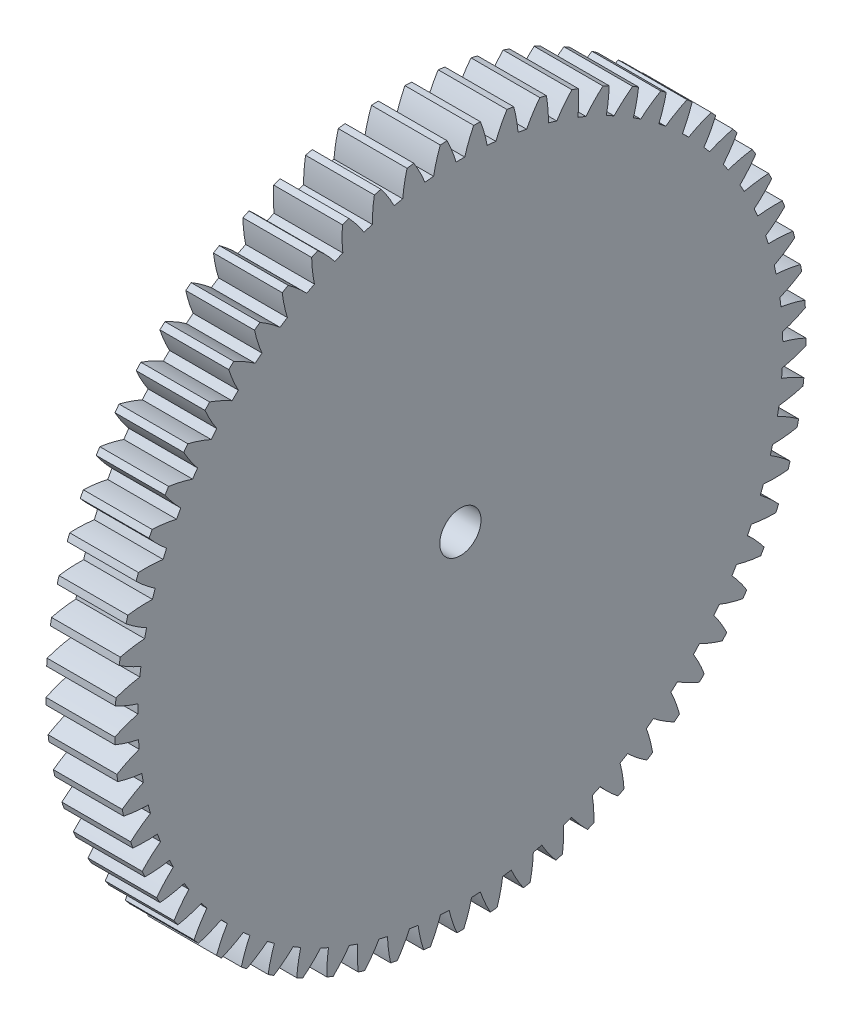
SolidWorks part; units mm, degrees
ref_plane "Plane1" through (0, 0, 0) normal (0, 0, 1) x (1, 0, 0)
ref_plane "Plane2" through (0, 0, 0) normal (0, 1, 0) x (1, 0, 0)
ref_plane "Plane3" through (0, 0, 0) normal (1, 0, 0) x (0, 0, -1)
other "Configuration Table"
sketch "HoldingSke" plane through (0, 0, 0) normal (0, 1, 0) x (1, 0, 0)
  line L0 (0, 0) -> (0.2817, -0.6042)
  line L1 (-15, 0) -> (100, 0) construction
  line L2 (0, 0) -> (-2.1039, 2.3779)
  line L3 (0, 0) -> (-11.863, 4.5341)
  line L4 (0, 0) -> (3.6497, 7.8269)
  line L5 (0, 0) -> (-46.8476, -17.4728)
  line L6 (0, 0) -> (-8.2896, -5.593)
  line L7 (-2.1039, 2.3779) -> (8.6586, 51.2059)
  line L8 (-76.2, 54.61) -> (-75.2, 54.61)
  line L9 (-71.009, 38.7566) -> (-53.1078, 45.2721)
  line L10 (-76.2, 71.12) -> (104.1128, 71.12)
  line L11 (0, 0) -> (-10, 0)
  line L12 (-76.2, 101.6) -> (-76.147, 101.6)
  line L13 (24.9733, 27.94) -> (52.9518, 28.4284)
  line L14 (24.9733, 27.94) -> (24.9743, 27.94)
  line L15 (24.9733, 27.94) -> (100.4006, 29.5858)
  line L16 (-63.627, -1.5) -> (-12.827, -1.5)
  circle A0 centre (0, 0) radius 3
  circle A1 centre (0, 0) radius 37.5
  circle A2 centre (0, 0) radius 37.5
  circle A3 centre (0, 0) radius 3
  dimension "MHD" = 75
  dimension "Hub_dia" = 75
  dimension "Bore" = 6
  dimension "MBD" = 6
  dimension "Num_teeth" = 65
  dimension "Overall_len" = 50
  dimension "Show_teeth" = 65
  dimension "Thickness" = 10
  dimension "OAL" = 50.0001
  dimension "T_dim" = 1
  dimension "Ap" = 20
  dimension "H" = 19.05
  dimension "Pitch_radius" = 180.3128
  dimension "Width" = 10
  dimension "Backlash" = 0.053
  dimension "Addendum_fac" = 1
  dimension "Dedendum_fac" = 1.25
  dimension "Clearance_fac" = 0.25
  dimension "Dedendum_add" = 0.001
sketch "BasProSke" plane through (0, 0, 0) normal (0, 1, 0) x (1, 0, 0)
  line L0 (-10, 0) -> (60, 0) construction
  line L1 (0, 0) -> (0, 50.25)
  line L2 (0, 0) -> (10, 0)
  line L3 (10, 0) -> (10, 50.25)
  line L4 (10, 50.25) -> (0, 50.25)
  dimension "Thickness" = 10
revolve "Base-Revolve" add sketch "BasProSke" angle 360 about L0
sketch "TooCutSke" plane through (0, 0, 0) normal (1, 0, 0) x (0, 0, -1)
  line L1 (0, 0) -> (0, 107) construction
  line L2 (0, 0) -> (-1.2707, 48.7334) construction
  line L3 (0, 0) -> (-4.7094, 97.362) construction
  line L4 (-1.2707, 48.7334) -> (-2.3547, 48.681) construction
  arc A0 (0.6342, 46.8697) -> (-0.6342, 46.8697) centre (0, 0) ccw
  arc A1 (1.9459, 50.2377) -> (-1.9459, 50.2377) centre (0, 0) ccw
  circle A2 centre (0, 0) radius 48.75 construction
  circle A3 centre (0, 0) radius 45.81 construction
  arc A4 (-0.6342, 46.8697) -> (-1.9459, 50.2377) centre (-19.3825, 41.5075) ccw
  arc A5 (1.9459, 50.2377) -> (0.6342, 46.8697) centre (19.3825, 41.5075) ccw
  dimension "Half_ang" = 2.769
extrude "ToothCut" cut sketch "TooCutSke" along normal through all
fillet "Breaks" [suppressed] radius 0.03
fillet "RootFillets" [suppressed] radius 0.376
pattern_circular "TeethCuts" count 65 every 5.538 about axis through (-10, 0, 0) along (1, 0, 0) of "ToothCut", "RootFillets", "Breaks"
sketch "HubNeaOneSke" plane through (0, 0, 0) normal (-1, 0, 0) x (0, 0, 1)
  circle A0 centre (0, 0) radius 37.5
  dimension "Diameter" = 75
extrude "HubNearOne" [suppressed] add sketch "HubNeaOneSke" along normal blind 40.0001
sketch "HubNeaBotSke" plane through (0, 0, 0) normal (-1, 0, 0) x (0, 0, 1)
  circle A0 centre (0, 0) radius 37.5
  dimension "Diameter" = 75
extrude "HubNearBoth" [suppressed] add sketch "HubNeaBotSke" along normal blind 20
ref_plane "FarPln" through (10, 0, 0) normal (1, 0, 0) x (0, 0, -1)
sketch "HubFarSke" plane through (10, 0, 0) normal (1, 0, 0) x (0, 0, -1)
  circle A0 centre (0, 0) radius 37.5
  dimension "Diameter" = 75
extrude "HubFar" [suppressed] add sketch "HubFarSke" along normal blind 20
sketch "BorSke" plane through (0, 0, 0) normal (1, 0, 0) x (0, 0, -1)
  circle A0 centre (0, 0) radius 3
  dimension "Diameter" = 6
extrude "Bore" cut sketch "BorSke" along normal mid plane 100.0001
sketch "KeySke" plane through (0, 0, 0) normal (1, 0, 0) x (0, 0, -1)
  line L0 (-1, 0) -> (-1, 4)
  line L1 (-1, 4) -> (1, 4)
  line L2 (1, 4) -> (1, 0)
  line L3 (0, 0) -> (0, 34) construction
  line L4 (-1, 0) -> (1, 0)
  dimension "Offset" = 4
  dimension "Width" = 2
extrude "Keyway" [suppressed] cut sketch "KeySke" along normal mid plane 100.0001
pattern_circular "Keyway2" [suppressed] count 2 every 90 about axis through (-10, 0, 0) along (1, 0, 0)
equation "' \"Module@HoldingSke\" = 6.35"
equation "' \"Num_teeth@HoldingSke\" = 12"
equation "' \"Ap@HoldingSke\" =  20"
equation "' \"Ap@HoldingSke\" = 20"
equation "' \"Width@HoldingSke\" = 0.5 * 25.4"
equation "' \"Hub_dia@HoldingSke\"= 1 * 25.4"
equation "' \"Hub_dia@HoldingSke\" = 1 * 25.4"
equation "' \"Overall_len@HoldingSke\" = 1.0 * 25.4"
equation "' \"Bore@HoldingSke\" = 0.75 * 25.4"
equation "' \"T_dim@HoldingSke\" = 0.1 * 25.4"
equation "' \"Width@KeySke\" = 0.25 * 25.4"
equation "' \"Show_teeth@HoldingSke\" = 13"
equation "' \"Backlash@HoldingSke\" = 0.009 * 25.4"
equation "' \"Addendum_fac@HoldingSke\" = 1.0"
equation "' \"Dedendum_fac@HoldingSke\" = 1.25"
equation "' \"Dedendum_add@HoldingSke\" = 0.00005 * 25.4"
equation "' \"Clearance_fac@HoldingSke\" = 0.25"
equation "\"Pitch@HoldingSke\" = 1 / \"Module@HoldingSke\""
equation "\"Overcut_dia@TooCutSke\" = (\"Num_teeth@HoldingSke\" + 2 * \"Addendum_fac@HoldingSke\") / \"Pitch@HoldingSke\" + 0.002 * 25.4"
equation "\"Pitch_dia@TooCutSke\" = \"Num_teeth@HoldingSke\" / \"Pitch@HoldingSke\""
equation "\"Base_dia@TooCutSke\" = \"Num_teeth@HoldingSke\" / \"Pitch@HoldingSke\" * cos((\"Ap@HoldingSke\"  * 3.14159265 / 180))"
equation "\"Root_dia@TooCutSke\" = (\"Num_teeth@HoldingSke\" + 2) / \"Pitch@HoldingSke\" - 2 * (\"Addendum_fac@HoldingSke\" + \"Dedendum_fac@HoldingSke\") / \"Pitch@HoldingSke\" - \"Dedendum_add@HoldingSke\" * 2"
equation "\"Half_ang@TooCutSke\" = 180 / \"Num_teeth@HoldingSke\""
equation "\"Half_CT@TooCutSke\" = \"Num_teeth@HoldingSke\" / \"Pitch@HoldingSke\" * sin((3.14159265 / 2 / \"Num_teeth@HoldingSke\")) / 2 - 7 * \"Backlash@HoldingSke\" / 4"
equation "\"Flank_rad@TooCutSke\" = \"Num_teeth@HoldingSke\" / \"Pitch@HoldingSke\" / 5"
equation "\"Radius@RootFillets\" = \"Clearance_fac@HoldingSke\" / \"Pitch@HoldingSke\" + \"Dedendum_add@HoldingSke\""
equation "\"Break_rad@Breaks\" = 0.02 / \"Pitch@HoldingSke\""
equation "\"Thickness@HoldingSke\" = \"Width@HoldingSke\""
equation "\"OAL@HoldingSke\" = \"Thickness@HoldingSke\""
equation "\"MHD@HoldingSke\" = (\"Num_teeth@HoldingSke\" + 2) / \"Pitch@HoldingSke\" - 2 * (\"Addendum_fac@HoldingSke\" + \"Dedendum_fac@HoldingSke\")  / \"Pitch@HoldingSke\" - \"Dedendum_add@HoldingSke\" * 2"
equation "\"MBD@HoldingSke\" = (\"Num_teeth@HoldingSke\" + 2) / \"Pitch@HoldingSke\" - 2 * (\"Addendum_fac@HoldingSke\" + \"Dedendum_fac@HoldingSke\")  / \"Pitch@HoldingSke\" - \"Dedendum_add@HoldingSke\" * 2 - 0.002 * 25.4"
equation "\"MHD@HoldingSke\" = ((sgn( \"MHD@HoldingSke\" - \"Hub_dia@HoldingSke\" )-1)*( \"MHD@HoldingSke\" - \"Hub_dia@HoldingSke\" ))/-2+ \"Hub_dia@HoldingSke\""
equation "\"MBD@HoldingSke\" = ((sgn( \"MBD@HoldingSke\" - \"Bore@HoldingSke\" )-1)*( \"MBD@HoldingSke\" - \"Bore@HoldingSke\" ))/-2+ \"Bore@HoldingSke\""
equation "\"OAL@HoldingSke\" = ((sgn( \"OAL@HoldingSke\" - \"Overall_len@HoldingSke\" )+1)*( \"OAL@HoldingSke\" - \"Overall_len@HoldingSke\" ))/2 + \"Overall_len@HoldingSke\" + 0.000002 * 25.4"
equation "\"Num_teeth@TeethCuts\" = int( \"Show_teeth@HoldingSke\" ) + 1"
equation "\"Num_teeth@TeethCuts\" = ((sgn( \"Num_teeth@TeethCuts\" - \"Num_teeth@HoldingSke\" )-1)*( \"Num_teeth@TeethCuts\" - \"Num_teeth@HoldingSke\" ))/-2+ \"Num_teeth@HoldingSke\""
equation "\"Num_teeth@TeethCuts\" = ((sgn( \"Num_teeth@TeethCuts\" - 2.0)+1)*( \"Num_teeth@TeethCuts\" - 2.0))/2 +2.0"
equation "\"Angle@TeethCuts\" = 360.0 / \"Num_teeth@HoldingSke\""
equation "\"Diameter@BasProSke\" = (\"Num_teeth@HoldingSke\" + 2 * \"Addendum_fac@HoldingSke\") / \"Pitch@HoldingSke\""
equation "\"Thickness@BasProSke\"  = \"Thickness@HoldingSke\""
equation "' \"Fillet_rad@BasProSke\" =  \"Thickness@HoldingSke\" * 0.05"
equation "' \"Fillet_rad@BasProSke\" = \"Thickness@HoldingSke\" * 0.05"
equation "\"MHD@HoldingSke\" = ((sgn( \"MHD@HoldingSke\" - \"Root_dia@TooCutSke\" )-1)*( \"MHD@HoldingSke\" - \"Root_dia@TooCutSke\" ))/-2+ \"Root_dia@TooCutSke\""
equation "\"Diameter@HubNeaOneSke\" = \"MHD@HoldingSke\""
equation "\"Length@HubNearOne\" = \"OAL@HoldingSke\" - \"Thickness@BasProSke\""
equation "\"Diameter@HubNeaBotSke\" = \"MHD@HoldingSke\""
equation "\"Length@HubNearBoth\" = ( \"OAL@HoldingSke\" - \"Thickness@BasProSke\" ) / 2.0"
equation "\"Thickness@FarPln\" = \"Thickness@BasProSke\""
equation "\"Diameter@HubFarSke\" = \"MHD@HoldingSke\""
equation "\"Length@HubFar\" = ( \"OAL@HoldingSke\" - \"Thickness@BasProSke\" ) / 2.0"
equation "\"Diameter@BorSke\" = \"MBD@HoldingSke\""
equation "\"D1@Bore\" = \"OAL@HoldingSke\" * 2.0"
equation "\"D1@Keyway\" = \"OAL@HoldingSke\" * 2.0"
equation "\"Offset@KeySke\" = \"T_dim@HoldingSke\" + \"MBD@HoldingSke\" / 2.0"
